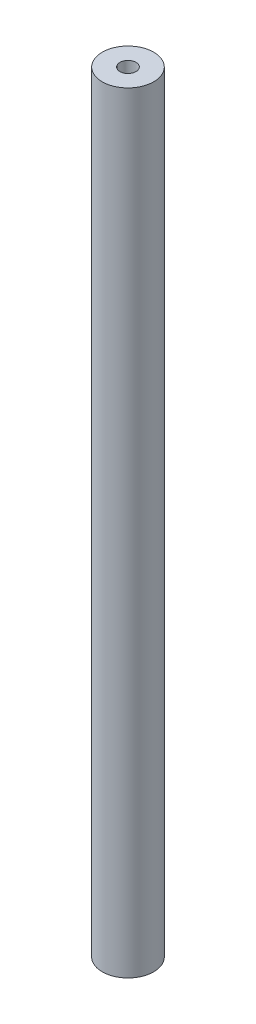
SolidWorks part; units mm, degrees
material "1060 合金"
ref_plane "前视基准面" through (0, 0, 0) normal (0, 0, 1) x (1, 0, 0)
ref_plane "上视基准面" through (0, 0, 0) normal (0, 1, 0) x (1, 0, 0)
ref_plane "右视基准面" through (0, 0, 0) normal (1, 0, 0) x (0, 0, -1)
sketch "草图1" plane through (0, 0, 0) normal (0, 1, 0) x (1, 0, 0)
  circle A0 centre (0, 0) radius 8
  dimension "D1" = 16
extrude "凸台-拉伸1" add sketch "草图1" along normal mid plane 240
sketch "草图2" plane through (0, 120, 0) normal (0, 1, 0) x (1, 0, 0)
  circle A0 centre (0, 0) radius 5
  dimension "D1" = 10
extrude "切除-拉伸1" [suppressed] cut sketch "草图2" against normal through all
hole_wizard "M6 螺纹孔1" positions "草图4" profile "草图3" tap size "M6" standard "GB"
sketch "草图4" plane through (0, 120, 0) normal (0, 1, 0) x (1, 0, 0)
  point P0 (0, 0)
sketch "草图3" plane through (0, 120, 0) normal (1, 0, 0) x (0, 0, 1)
  line L0 (0, 0) -> (0, 18.5022)
  line L1 (0, 18.5022) -> (2.5, 17)
  line L2 (2.5, 17) -> (2.5, 0)
  line L5 (2.5, 0) -> (0, 0)
  line L10 (0, 18.5022) -> (-2.5, 17) construction
  line L11 (0, -6.35) -> (0, 107.95) construction
  dimension "螺纹孔钻头直径" = 5
  dimension "螺纹孔钻头深度" = 17
  dimension "导头角度" = 118
cosmetic thread "孔螺蚊线1"
mirror "镜向1" about plane through (0, 0, 0) normal (0, 1, 0) of "M6 螺纹孔1"
